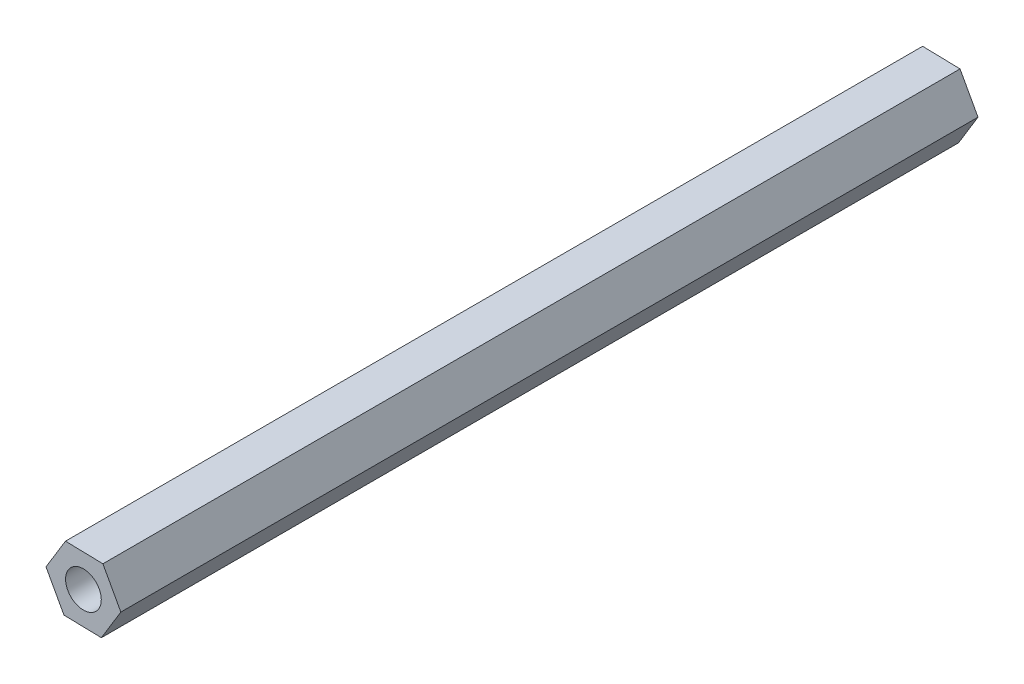
SolidWorks part; units mm, degrees
ref_plane "前视基准面" through (0, 0, 0) normal (0, 0, 1) x (1, 0, 0)
ref_plane "上视基准面" through (0, 0, 0) normal (0, 1, 0) x (1, 0, 0)
ref_plane "右视基准面" through (0, 0, 0) normal (1, 0, 0) x (0, 0, -1)
sketch "草图1" plane through (0, 0, 0) normal (0, 0, 1) x (1, 0, 0)
  line L1 (1.3632, 2.2374) -> (-1.2561, 2.2993)
  line L2 (-1.2561, 2.2993) -> (-2.6193, 0.0619)
  line L3 (-2.6193, 0.0619) -> (-1.3632, -2.2374)
  line L4 (-1.3632, -2.2374) -> (1.2561, -2.2993)
  line L5 (1.2561, -2.2993) -> (2.6193, -0.0619)
  line L6 (2.6193, -0.0619) -> (1.3632, 2.2374)
  circle A0 centre (0, 0) radius 2.62 construction
  dimension "D1" = 5.24
extrude "凸台-拉伸1" add sketch "草图1" along normal blind 60
hole_wizard "M3 螺纹孔1" positions "草图3" profile "草图2" tap size "M3" standard "GB"
sketch "草图3" plane through (0, 0, 60) normal (0, 0, 1) x (1, 0, 0)
  point P0 (0, 0)
sketch "草图2" plane through (0, 0, 60) normal (1, 0, 0) x (0, -1, 0)
  line L0 (0, 0) -> (0, 15.7511)
  line L1 (0, 15.7511) -> (1.25, 15)
  line L2 (1.25, 15) -> (1.25, 0)
  line L5 (1.25, 0) -> (0, 0)
  line L10 (0, 15.7511) -> (-1.25, 15) construction
  line L11 (0, -6.35) -> (0, 107.95) construction
  dimension "螺纹孔钻头直径" = 2.5
  dimension "螺纹孔钻头深度" = 15
  dimension "导头角度" = 118
cosmetic thread "孔螺蚊线1" parameters "D1"=12, "D2"=3
hole_wizard "M3 螺纹孔2" positions "草图5" profile "草图4" tap size "M3" standard "GB"
sketch "草图5" plane through (0, 0, 0) normal (0, 0, -1) x (-1, 0, 0)
  point P0 (0, 0)
sketch "草图4" plane through (0, 0, 0) normal (1, 0, 0) x (0, 1, 0)
  line L0 (0, 0) -> (0, 15.7511)
  line L1 (0, 15.7511) -> (1.25, 15)
  line L2 (1.25, 15) -> (1.25, 0)
  line L5 (1.25, 0) -> (0, 0)
  line L10 (0, 15.7511) -> (-1.25, 15) construction
  line L11 (0, -6.35) -> (0, 107.95) construction
  dimension "螺纹孔钻头直径" = 2.5
  dimension "螺纹孔钻头深度" = 15
  dimension "导头角度" = 118
cosmetic thread "孔螺蚊线2" parameters "D1"=12, "D2"=3
